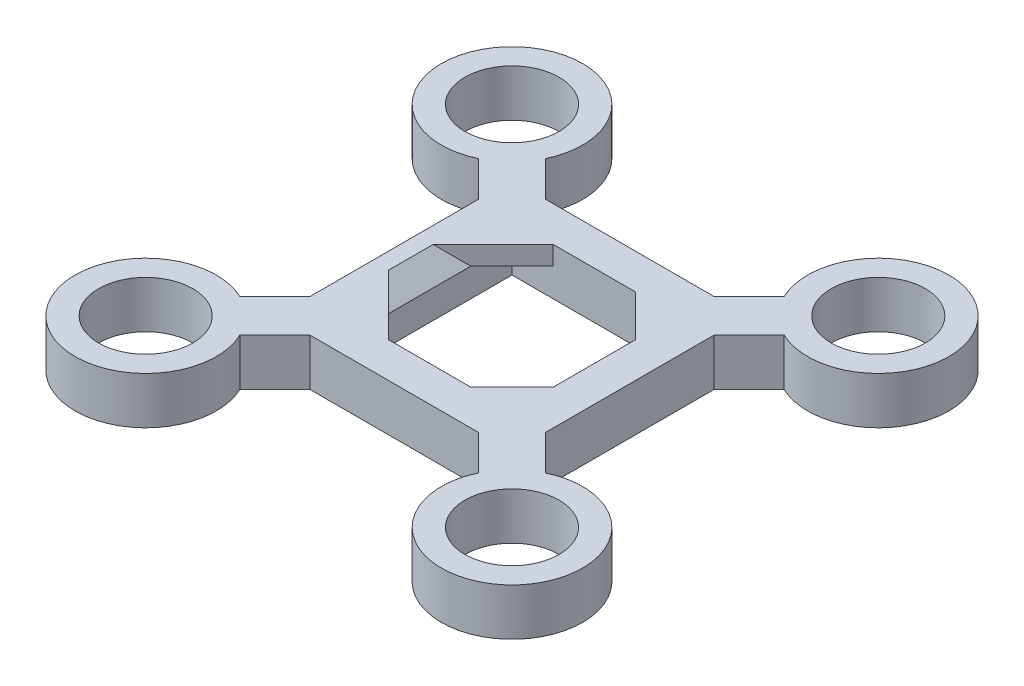
SolidWorks part; units mm, degrees
ref_plane "Front Plane" through (0, 0, 0) normal (0, 0, 1) x (1, 0, 0)
ref_plane "Top Plane" through (0, 0, 0) normal (0, 1, 0) x (1, 0, 0)
ref_plane "Right Plane" through (0, 0, 0) normal (1, 0, 0) x (0, 0, -1)
sketch "Sketch1" plane through (0, 0, 0) normal (0, 1, 0) x (1, 0, 0)
  line L0 (0, 0) -> (-5.3033, 5.3033) construction
  line L1 (-1.75, -1.75) -> (1.75, -1.75)
  line L2 (-1.75, -1.75) -> (-1.75, 1.75)
  line L3 (-1.75, 1.75) -> (1.75, 1.75)
  line L4 (1.75, -1.75) -> (1.75, 1.75)
  line L5 (-1.75, -1.75) -> (1.75, 1.75) construction
  line L6 (-1.75, 1.75) -> (1.75, -1.75) construction
  line L7 (-2.5, -2.5) -> (2.5, -2.5)
  line L8 (-2.5, -2.5) -> (-2.5, 2.5)
  line L9 (-2.5, 2.5) -> (2.5, 2.5)
  line L10 (2.5, -2.5) -> (2.5, 2.5)
  line L11 (-2.5, -2.5) -> (2.5, 2.5) construction
  line L12 (-2.5, 2.5) -> (2.5, -2.5) construction
  line L13 (-4.5962, 4.5962) -> (-4.9497, 4.2426) construction
  line L14 (-4.9497, 4.2426) -> (-2.5, 1.7929)
  line L15 (-4.2426, 4.9497) -> (-1.7929, 2.5)
  line L16 (-2.5, 0) -> (2.5, 0) construction
  line L17 (4.2426, -4.9497) -> (1.7929, -2.5)
  line L18 (4.9497, -4.2426) -> (2.5, -1.7929)
  line L19 (4.2426, 4.9497) -> (1.7929, 2.5)
  line L20 (4.9497, 4.2426) -> (2.5, 1.7929)
  line L21 (-4.2426, -4.9497) -> (-1.7929, -2.5)
  line L22 (-4.9497, -4.2426) -> (-2.5, -1.7929)
  circle A0 centre (-4.5962, 4.5962) radius 0.5
  circle A1 centre (4.5962, -4.5962) radius 0.5
  circle A2 centre (4.5962, 4.5962) radius 0.5
  circle A3 centre (-4.5962, -4.5962) radius 0.5
  point P0 (0, 0)
  point P6 (0, 0)
  dimension "D6" = 1
  dimension "D7" = 1
  dimension "D1" = 3.5
  dimension "D2" = 3.5
  dimension "D3" = 5
  dimension "D4" = 5
  dimension "D5" = 7.5
  dimension "D8" = 90
  dimension "D9" = 90
extrude "Boss-Extrude3" add sketch "Sketch1" along normal blind 1 contours A0 | A0 L14 L8 L9 L15 | L7 L10 L9 L8 L4 L1 L2 L3 | A2 L19 L9 L10 L20 | A2 | A1 | L17 A1 L18 L10 L7 | L22 A3 L21 L7 L8 | A3
sketch "Sketch4" plane through (0, 1, 0) normal (0, 1, 0) x (1, 0, 0)
  line L0 (-1.75, 0) -> (-1.75, 1.75) construction
  line L1 (-1.75, -1.75) -> (-1.75, 1.75) construction
  line L2 (0, 1.75) -> (-1.75, 1.75) construction
  line L3 (-1.75, 1.75) -> (1.75, 1.75) construction
  line L4 (-1.75, -1.75) -> (1.75, 1.75) construction
  line L5 (-1.75, 0.875) -> (-0.875, 1.75)
  line L6 (-0.875, 1.75) -> (-1.75, 1.75)
  line L7 (-1.75, 1.75) -> (-1.75, 0.875)
  line L8 (1.75, -0.875) -> (1.75, -1.75)
  line L9 (0.875, -1.75) -> (1.75, -0.875)
  line L10 (1.75, -1.75) -> (0.875, -1.75)
  line L11 (-1.75, 0) -> (1.75, 0) construction
  line L12 (1.75, -1.75) -> (1.75, 1.75) construction
  line L13 (0.875, 1.75) -> (1.75, 0.875)
  line L14 (1.75, 1.75) -> (0.875, 1.75)
  line L15 (1.75, 0.875) -> (1.75, 1.75)
  line L16 (-0.875, -1.75) -> (-1.75, -1.75)
  line L17 (-1.75, -0.875) -> (-0.875, -1.75)
  line L18 (-1.75, -1.75) -> (-1.75, -0.875)
extrude "Boss-Extrude4" add sketch "Sketch4" against normal blind 0.4
chamfer "Chamfer1" distance 0.4 angle 45 1 edges at (-1.75, 1, 0)
sketch "Sketch5" plane through (0, 1, 0) normal (0, 1, 0) x (1, 0, 0)
  line L0 (0, 0) -> (-4.5962, 4.5962) construction
  line L1 (0, 0) -> (-2.5, 0) construction
  line L2 (-2.5, -1.7929) -> (-2.5, 1.7929) construction
  line L3 (-4.9497, -4.9497) -> (0, 0) construction
  arc A1 (-4.9497, -4.2426) -> (-4.2426, -4.9497) centre (-4.5962, -4.5962) ccw construction
  circle A2 centre (-3.8891, 3.8891) radius 1.5
  circle A3 centre (3.8891, -3.8891) radius 1.5
  circle A4 centre (3.8891, 3.8891) radius 1.5
  circle A5 centre (-3.8891, -3.8891) radius 1.5
  dimension "D1" = 1
  dimension "D3" = 3
extrude "Boss-Extrude5" add sketch "Sketch5" against normal blind 1
sketch "Sketch6" plane through (0, 1, 0) normal (0, 1, 0) x (1, 0, 0)
  line L0 (0, 0) -> (-3.8891, 3.8891) construction
  line L1 (0, 0) -> (3.8891, 3.8891) construction
  line L2 (0, 0) -> (-2.5, 0) construction
  line L3 (-2.5, -1.7929) -> (-2.5, 1.7929) construction
  circle A0 centre (-3.8891, 3.8891) radius 1
  circle A1 centre (3.8891, -3.8891) radius 1
  circle A2 centre (3.8891, 3.8891) radius 1
  circle A3 centre (-3.8891, -3.8891) radius 1
  dimension "D1" = 2
extrude "Cut-Extrude1" cut sketch "Sketch6" against normal blind 1
